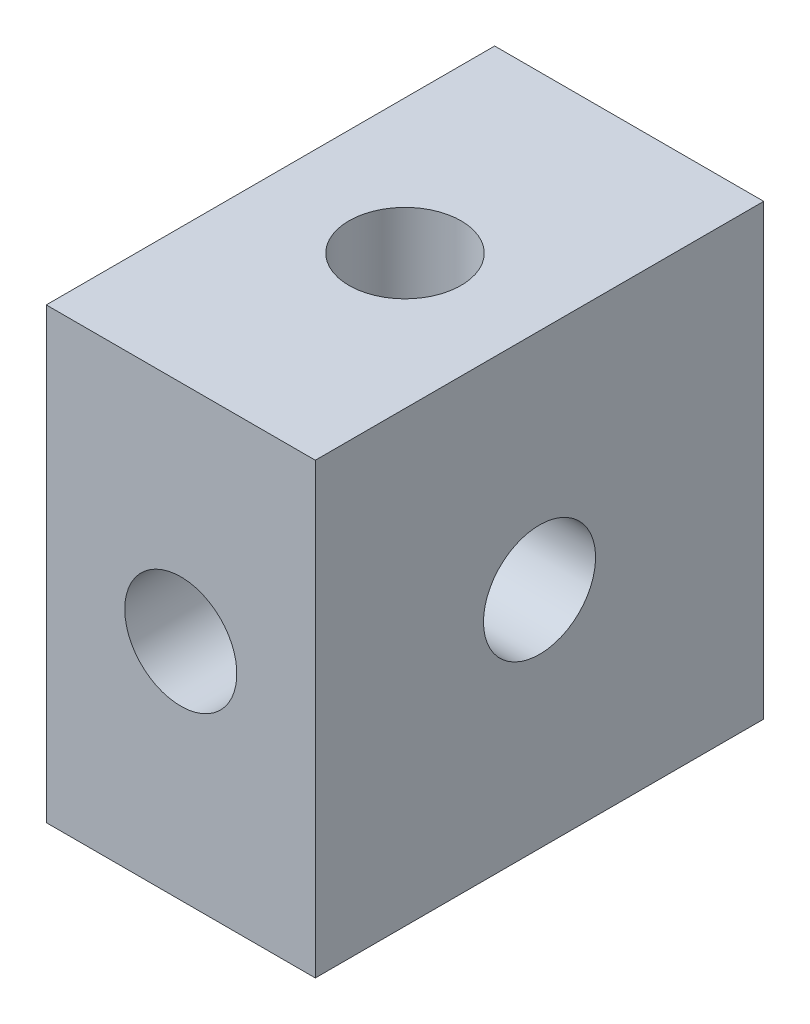
SolidWorks part; units mm, degrees
material "6061-T6 (SS)"
ref_plane "前视基准面" through (0, 0, 0) normal (0, 0, 1) x (1, 0, 0)
ref_plane "上视基准面" through (0, 0, 0) normal (0, 1, 0) x (1, 0, 0)
ref_plane "右视基准面" through (0, 0, 0) normal (1, 0, 0) x (0, 0, -1)
sketch "草图1" plane through (0, 0, 0) normal (0, 0, 1) x (1, 0, 0)
  line L1 (3, -5) -> (-3, -5)
  line L2 (3, -5) -> (3, 5)
  line L3 (3, 5) -> (-3, 5)
  line L4 (-3, -5) -> (-3, 5)
  line L5 (3, -5) -> (-3, 5) construction
  line L6 (3, 5) -> (-3, -5) construction
  point P0 (0, 0)
  dimension "D1" = 6
  dimension "D2" = 10
extrude "凸台-拉伸1" add sketch "草图1" along normal blind 10
sketch "草图2" plane through (0, 5, 0) normal (0, 1, 0) x (1, 0, 0)
  line L0 (3, -5) -> (-4.0873, -5) construction
  line L1 (3, -10) -> (3, 0) construction
  line L2 (0, 0) -> (0, -10.3163) construction
  circle A0 centre (0, -5) radius 1.25
  dimension "D1" = 2.5
extrude "切除-拉伸1" cut sketch "草图2" against normal through all
cosmetic thread "装饰螺纹线1" parameters "D2"=3
cosmetic thread "装饰螺纹线2" parameters "D2"=3
sketch "草图3" plane through (0, 0, 0) normal (0, 0, -1) x (-1, 0, 0)
  line L0 (0, 5) -> (0, -5.6004) construction
  line L1 (-3, 5) -> (3, 5) construction
  line L2 (3, 0) -> (-3.5328, 0) construction
  line L3 (3, 5) -> (3, -5) construction
  circle A0 centre (0, 0) radius 1.25
  dimension "D1" = 2.5
extrude "切除-拉伸2" cut sketch "草图3" against normal through all
cosmetic thread "装饰螺纹线3" parameters "D2"=3
sketch "草图5" plane through (-3, 0, 0) normal (-1, 0, 0) x (0, 0, 1)
  line L0 (0, 0) -> (11.8543, 0) construction
  line L1 (5, -5) -> (5, 5.6956) construction
  line L2 (10, -5) -> (0, -5) construction
  circle A0 centre (5, 0) radius 1.25
  dimension "D1" = 2.5
extrude "切除-拉伸3" cut sketch "草图5" against normal through all
cosmetic thread "装饰螺纹线4" parameters "D2"=3
cosmetic thread "装饰螺纹线5" parameters "D2"=3
cosmetic thread "装饰螺纹线6" parameters "D2"=3
